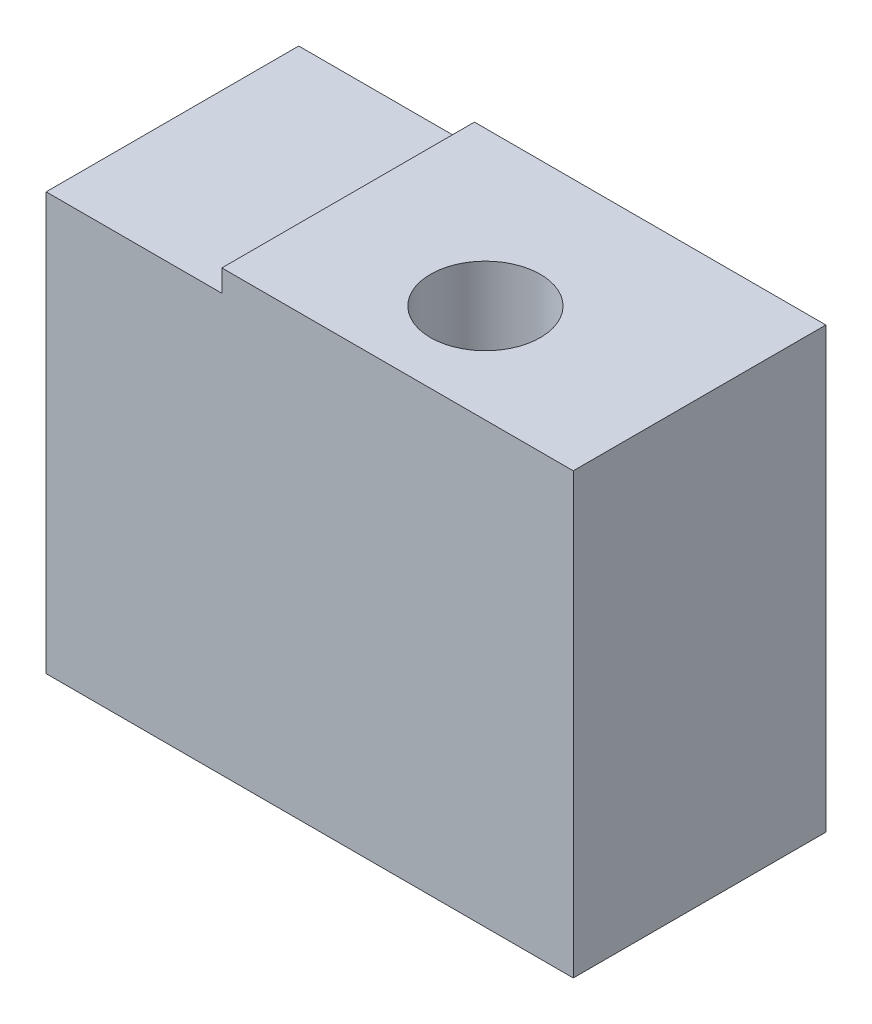
SolidWorks part; units mm, degrees
ref_plane "Front" through (0, 0, 0) normal (0, 0, 1) x (1, 0, 0)
ref_plane "Top" through (0, 0, 0) normal (0, 1, 0) x (1, 0, 0)
ref_plane "Right" through (0, 0, 0) normal (1, 0, 0) x (0, 0, -1)
sketch "Sketch1" plane through (0, 0, 0) normal (0, 0, 1) x (1, 0, 0)
  line L0 (0, 0) -> (24, 0)
  line L1 (24, 0) -> (24, 20)
  line L2 (24, 20) -> (8, 20)
  line L3 (8, 20) -> (8, 19)
  line L4 (8, 19) -> (0, 19)
  line L5 (0, 19) -> (0, 0)
  dimension "D1" = 24
  dimension "D2" = 20
  dimension "D3" = 8
  dimension "D4" = 19
extrude "Boss-Extrude1" add sketch "Sketch1" along normal blind 11.5
hole_wizard "M6x1.0 Tapped Hole1" positions "Sketch3" profile "Sketch4" tap size "M6x1.0" standard "ANSI Metric" end condition through all
sketch "Sketch3" plane through (0, 20, 0) normal (0, 1, 0) x (1, 0, 0)
  line L0 (24, -11.5) -> (8, -11.5) construction
  line L2 (0, -11.5) -> (0, 0) construction
  point P0 (15.5, -7)
  point P9 (0, -6.2477)
  dimension "D1" = 4.5
  dimension "D2" = 15.5
sketch "Sketch4" plane through (15.5, 20, 7) normal (1, 0, 0) x (0, 0, 1)
  line L0 (0, 0) -> (0, 20)
  line L1 (0, 20) -> (2.5, 20)
  line L2 (2.5, 20) -> (2.5, 0)
  line L5 (2.5, 0) -> (0, 0)
  line L11 (0, -6.35) -> (0, 107.95) construction
  dimension "Thru Tap Drill Dia." = 5
  dimension "Thru Tap Drill Depth" = 20
cosmetic thread "Hole Thread1"
